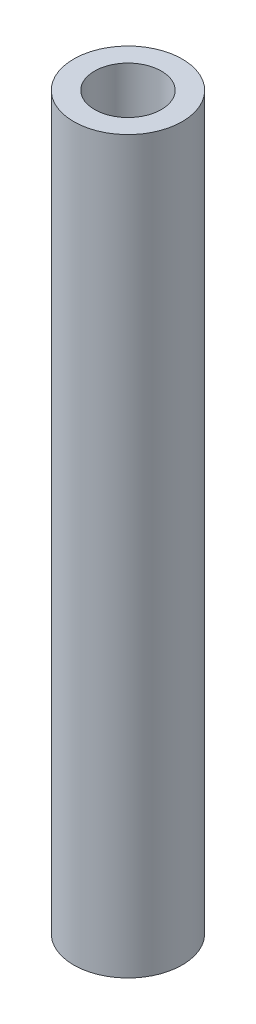
SolidWorks part; units mm, degrees
ref_plane "Front Plane" through (0, 0, 0) normal (0, 0, 1) x (1, 0, 0)
ref_plane "Top Plane" through (0, 0, 0) normal (0, 1, 0) x (1, 0, 0)
ref_plane "Right Plane" through (0, 0, 0) normal (1, 0, 0) x (0, 0, -1)
sketch "Sketch1" plane through (0, 3, 0) normal (0, 1, 0) x (1, 0, 0)
  circle A0 centre (-20, 25) radius 1.6
  circle A1 centre (-20, 25) radius 2.6
extrude "Boss-Extrude1" add sketch "Sketch1" along normal blind 35
